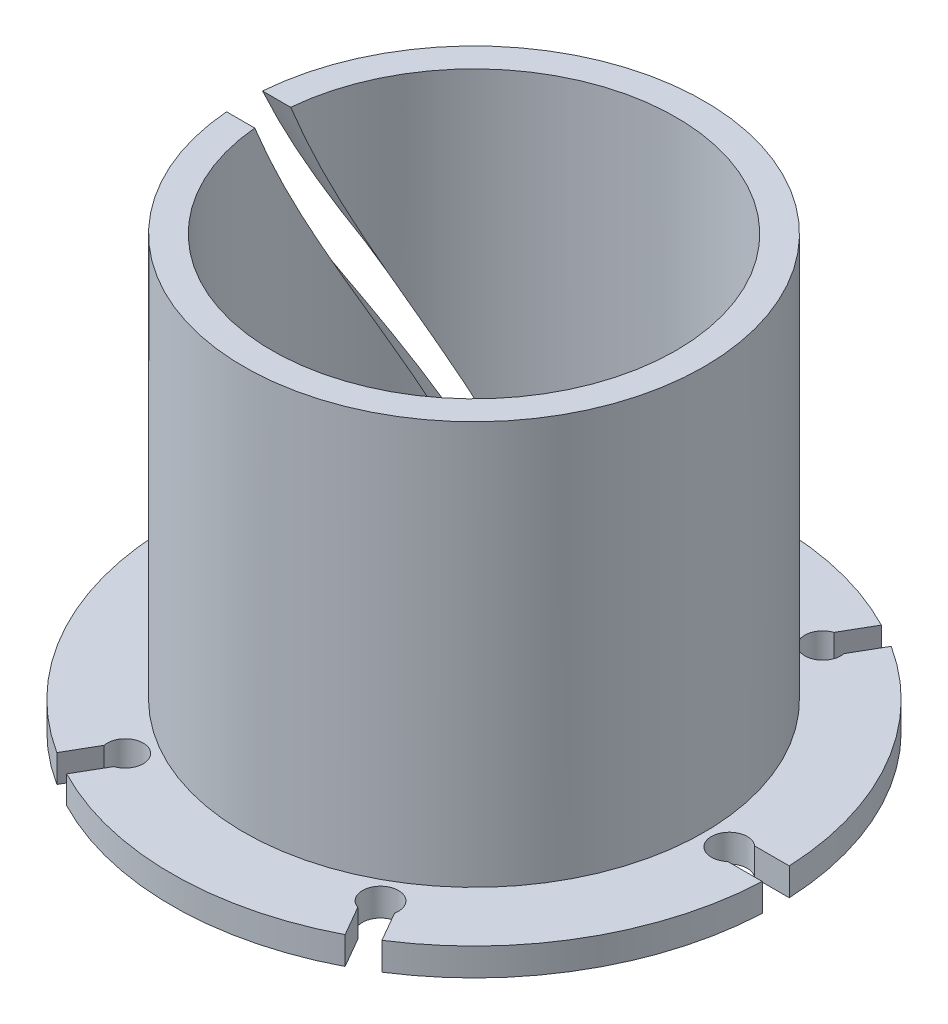
SolidWorks part; units mm, degrees
ref_plane "Front" through (0, 0, 0) normal (0, 0, 1) x (1, 0, 0)
ref_plane "Top" through (0, 0, 0) normal (0, 1, 0) x (1, 0, 0)
ref_plane "Right" through (0, 0, 0) normal (1, 0, 0) x (0, 0, -1)
sketch "Sketch1" plane through (0, 0, 0) normal (0, 1, 0) x (1, 0, 0)
  circle A0 centre (0, 0) radius 5.5753
  circle A1 centre (0, 0) radius 6.35
  circle A2 centre (0, 0) radius 8.3344
  dimension "ID" = 11.1506
  dimension "OD" = 12.7
  dimension "FlangeOD" = 16.6687
sketch "Sketch2" plane through (0, 0, 0) normal (0, 1, 0) x (1, 0, 0)
  circle A0 centre (0, 0) radius 5.5753 construction
  circle A1 centre (0, 0) radius 6.35 construction
  circle A2 centre (0, 0) radius 5.5753
  circle A3 centre (0, 0) radius 6.35
extrude "Boss-Extrude1" add sketch "Sketch2" along normal blind 11.8872
sketch "Sketch3" plane through (0, 0, 0) normal (0, 1, 0) x (1, 0, 0)
  circle A0 centre (0, 0) radius 8.3344 construction
  circle A1 centre (0, 0) radius 6.35 construction
  circle A2 centre (0, 0) radius 8.3344
  circle A3 centre (0, 0) radius 6.35
extrude "Boss-Extrude2" add sketch "Sketch3" along normal blind 0.762
sketch "Sketch5" plane through (0, 11.8872, 0) normal (0, 1, 0) x (1, 0, 0)
  circle A0 centre (0, 0) radius 6.35 construction
  circle A1 centre (0, 0) radius 6.35
curve "Helix/Spiral1" pitch 47.5488 height 11.8872 turns 0.25
sketch "Sketch7" plane through (0, 0.762, 0) normal (0, 1, 0) x (1, 0, 0)
  line L0 (-6.35, 0) -> (-8.3344, 0) construction
  line L1 (-7.3727, 0.3721) -> (-8.3344, 0.3721)
  line L2 (-8.3344, 0.3721) -> (-8.3344, -0.3721)
  line L3 (-8.3344, -0.3721) -> (-7.3727, -0.3721)
  line L4 (-4.4853, 7.0245) -> (-3.8408, 7.3966) construction
  line L5 (-4.4853, 7.0245) -> (-3.8445, 5.9147) construction
  line L6 (-3.8408, 7.3966) -> (-3.2, 6.2868) construction
  line L7 (-3.5223, 6.1007) -> (0, 0) construction
  line L8 (-3.8445, 5.9147) -> (-3.2, 6.2868) construction
  circle A0 centre (0, 0) radius 7.0445 construction
  circle A1 centre (0, 0) radius 6.35 construction
  circle A2 centre (0, 0) radius 8.3344 construction
  arc A3 (-7.3727, -0.3721) -> (-7.3727, 0.3721) centre (-7.0445, 0) ccw
  circle A4 centre (-3.5223, 6.1007) radius 0.4961 construction
  circle A5 centre (0, 0) radius 8.3344 construction
  point P9 (-7.0445, 0)
  dimension "D2" = 0.9922
  dimension "D1" = 1.9844
  dimension "D3" = 0.7441
  dimension "D4" = 1.2898
  dimension "D6" = 60
extrude "Cut-Extrude1" cut sketch "Sketch7" against normal through all
pattern_circular "CirPattern1" count 6 over 360 about axis through (0, 11.8872, 0) along (0, -1, 0) skipping 1 of "Cut-Extrude1"
ref_plane "Plane1" through (0, 5.9436, 0) normal (0, 1, 0) x (-1, 0, 0)
sketch "Sketch9" plane through (0, 11.8872, 0) normal (0, 1, 0) x (1, 0, 0)
  circle A1 centre (0, 0) radius 6.35
  circle A2 centre (0, 0) radius 6.35
  point P0 (-6.35, 0)
  dimension "D1" = 0
sketch "Sketch10" plane through (0, 0, 0) normal (0, -1, 0) x (1, 0, 0)
  line L0 (-3.5223, -6.1007) -> (0, 0) construction
  circle A0 centre (0, 0) radius 6.35 construction
  circle A1 centre (0, 0) radius 6.35
  point P3 (-3.175, -5.4993)
sketch "Sketch11" plane through (0, 5.9436, 0) normal (0, 1, 0) x (-1, 0, 0)
  line L0 (0, 0) -> (7.0445, 0) construction
  line L1 (0, 0) -> (3.5223, -6.1007) construction
  line L2 (0, 0) -> (5.4993, -3.175) construction
  circle A0 centre (0, 0) radius 6.35 construction
  circle A1 centre (0, 0) radius 6.35
  point P3 (5.4993, -3.175)
  dimension "D1" = 30
sketch3d "3DSketch1"
  spline S0 degree 2 poles (-6.35, 11.8872, 0) (-6.236, 5.9436, -3.6004) (-3.175, 0, -5.4993) knots 0 0 0 1 1 1
sketch "Sketch12" plane through (0, 11.8872, 0) normal (0, 1, 0) x (1, 0, 0)
  line L1 (-10.8744, 0.4961) -> (-5.5532, 0.4961)
  line L2 (-10.8744, 0.4961) -> (-10.8744, -0.4961)
  line L3 (-10.8744, -0.4961) -> (-5.5532, -0.4961)
  line L4 (-5.5532, 0.4961) -> (-5.5532, -0.4961)
  arc A0 (-7.3727, -0.3721) -> (-7.3727, 0.3721) centre (-7.0445, 0) ccw construction
  circle A1 centre (0, 0) radius 5.5753 construction
  dimension "D1" = 2.54
sketch "Sketch13" plane through (0, 0, 0) normal (0, -1, 0) x (1, 0, 0)
  line L0 (-3.2062, -4.5612) -> (-5.8668, -9.1694)
  line L1 (-3.2062, -4.5612) -> (-2.347, -5.0572)
  line L2 (-5.8668, -9.1694) -> (-5.0076, -9.6655)
  line L3 (-2.347, -5.0572) -> (-5.0076, -9.6655)
  line L4 (0, 0) -> (-3.5223, -6.1007) construction
  line L5 (-10.8744, -0.4961) -> (-5.5532, -0.4961) construction
  circle A0 centre (0, 0) radius 5.5753 construction
  circle A1 centre (-3.5223, -6.1007) radius 0.4961 construction
loft "Cut-Loft1" cut profiles "Sketch13", "Sketch12"
equation "\"D2@Sketch7\" = \"D1@Sketch7\"*.5"
equation "\"D3@Sketch7\" = \"D2@Sketch7\"*.75"
equation "\"D4@Sketch7\" = \"D1@Sketch7\"*.65"
equation "\"D3@Helix/Spiral1\" = \"Length@Boss-Extrude1\""
equation "\"D1@Plane1\" = \"Length@Boss-Extrude1\"/2"
